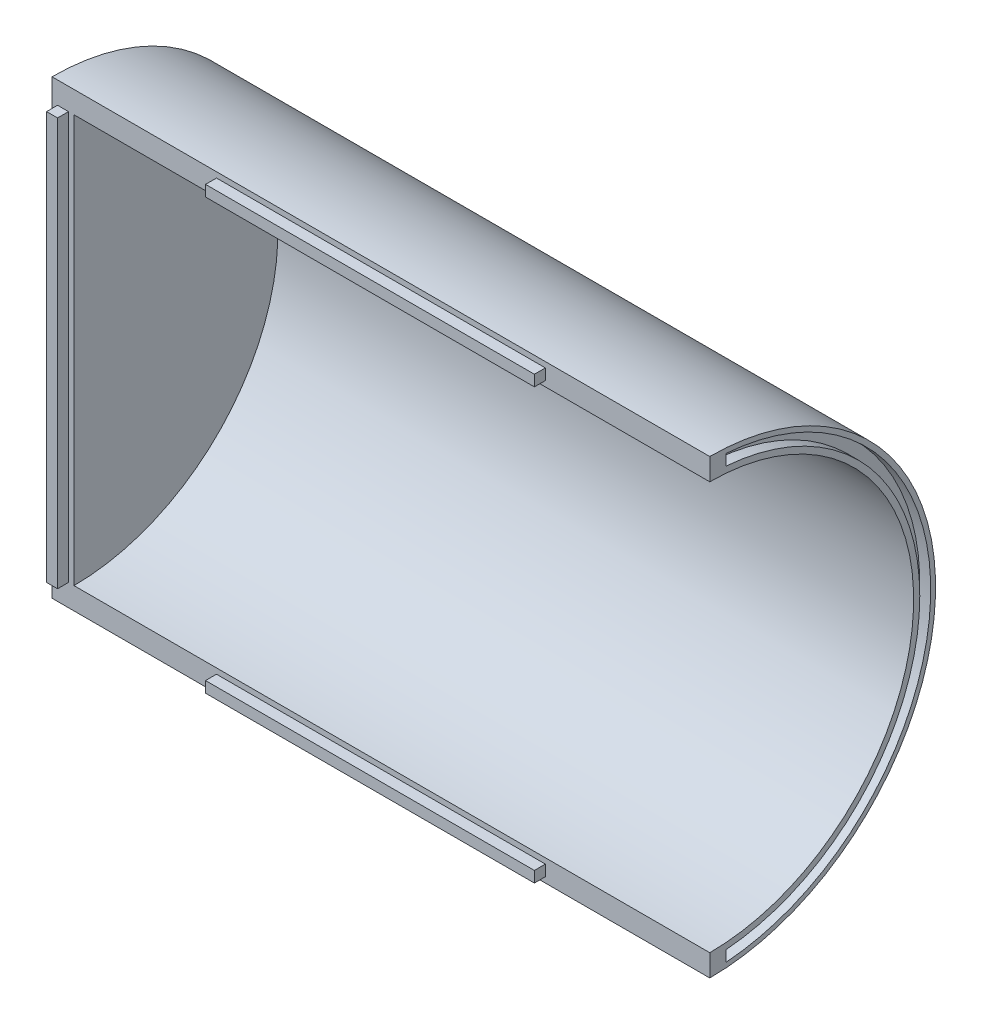
SolidWorks part; units mm, degrees
ref_plane "Front Plane" through (0, 0, 0) normal (0, 0, 1) x (1, 0, 0)
ref_plane "Top Plane" through (0, 0, 0) normal (0, 1, 0) x (1, 0, 0)
ref_plane "Right Plane" through (0, 0, 0) normal (1, 0, 0) x (0, 0, -1)
sketch "Sketch1" plane through (0, 0, 0) normal (0, 0, 1) x (1, 0, 0)
  line L0 (0, 0) -> (0, 52.324)
  line L1 (0, 52.324) -> (152.4, 52.324)
  line L2 (152.4, 52.324) -> (152.4, 47.244)
  line L3 (152.4, 47.244) -> (5.08, 47.244)
  line L4 (5.08, 47.244) -> (5.08, 0)
  line L5 (5.08, 0) -> (0, 0)
  dimension "D1" = 52.324
  dimension "D2" = 152.4
  dimension "D3" = 5.08
  dimension "D4" = 5.08
revolve "Revolve1" add sketch "Sketch1" angle 180 about L5
sketch "Sketch4" plane through (0, 0, 0) normal (0, 0, 1) x (1, 0, 0)
  line L0 (5.08, -47.244) -> (0, -47.244) construction
  line L1 (3.81, -47.244) -> (1.27, -47.244)
  line L2 (3.81, -47.244) -> (3.81, 47.244)
  line L3 (3.81, 47.244) -> (1.27, 47.244)
  line L4 (1.27, -47.244) -> (1.27, 47.244)
  line L5 (0, -52.324) -> (0, 52.324) construction
  line L9 (152.4, 52.324) -> (0, 52.324) construction
  line L10 (38.1, 48.514) -> (114.3, 48.514)
  line L11 (38.1, 48.514) -> (38.1, 51.054)
  line L12 (38.1, 51.054) -> (114.3, 51.054)
  line L13 (114.3, 48.514) -> (114.3, 51.054)
  line L14 (152.4, 52.324) -> (152.4, 47.244) construction
  line L15 (0, 0) -> (152.4, 0) construction
  line L16 (152.4, -47.244) -> (152.4, 47.244) construction
  line L17 (38.1, -51.054) -> (114.3, -51.054)
  line L18 (114.3, -48.514) -> (114.3, -51.054)
  line L19 (38.1, -48.514) -> (114.3, -48.514)
  line L20 (38.1, -48.514) -> (38.1, -51.054)
  point P9 (2.54, -47.244)
  point P10 (2.54, -47.244)
  point P17 (76.2, 52.324)
  point P18 (76.2, 51.054)
  point P23 (152.4, 49.784)
  point P24 (114.3, 49.784)
  dimension "D1" = 2.54
  dimension "D2" = 94.488
  dimension "D3" = 2.54
  dimension "D4" = 76.2
extrude "Boss-Extrude1" add sketch "Sketch4" along normal blind 2.54 contours L17 L18 L19 L20 | L2 L1 L4 L3 | L11 L10 L13 L12
sketch "Sketch5" plane through (152.4, 0, 0) normal (1, 0, 0) x (0, 0, -1)
  line L0 (3.81, 51.054) -> (3.81, 48.514)
  line L1 (0, 0) -> (52.324, 0) construction
  line L2 (3.81, -51.054) -> (3.81, -48.514)
  line L3 (0, 52.324) -> (0, 47.244) construction
  line L4 (0, 48.514) -> (3.81, 48.514) construction
  arc A0 (3.81, -51.054) -> (3.81, 51.054) centre (0, 0) ccw
  arc A1 (3.81, -48.514) -> (3.81, 48.514) centre (0, 0) ccw
  arc A2 (0, -52.324) -> (0, 52.324) centre (0, 0) ccw construction
  point P14 (3.81, 49.784)
  point P15 (0, 49.784)
  dimension "D2" = 3.81
  dimension "D1" = 2.54
extrude "Cut-Extrude1" cut sketch "Sketch5" against normal blind 2.54 contours A0 L0 A1 L2
